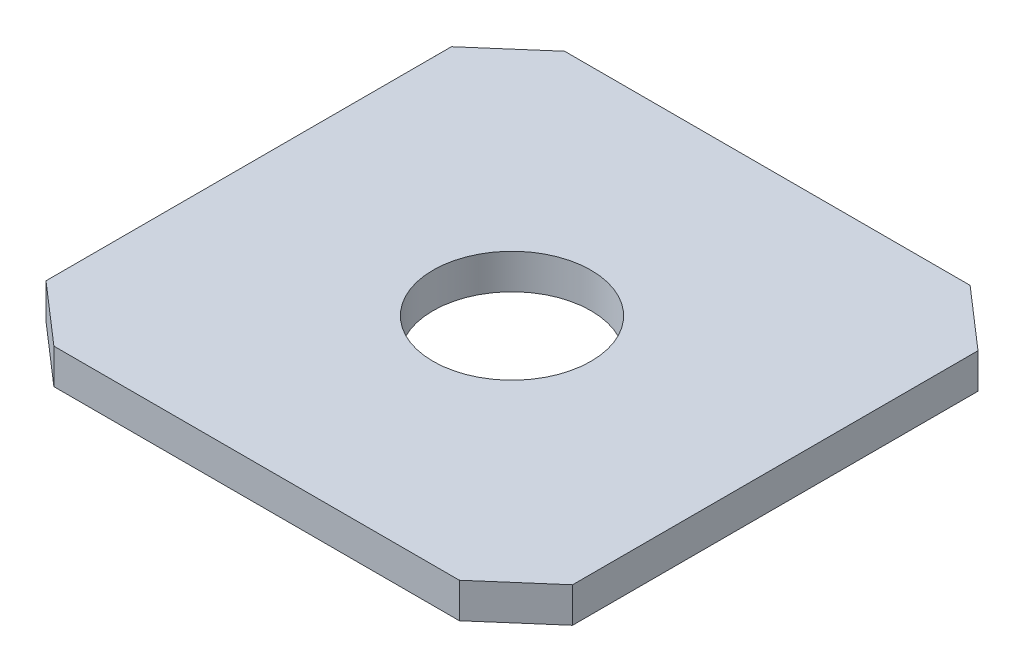
SolidWorks part; units mm, degrees
ref_plane "Front Plane" through (0, 0, 0) normal (0, 0, 1) x (1, 0, 0)
ref_plane "Top Plane" through (0, 0, 0) normal (0, 1, 0) x (1, 0, 0)
ref_plane "Right Plane" through (0, 0, 0) normal (1, 0, 0) x (0, 0, -1)
sketch "Sketch1" plane through (0, 0, 0) normal (0, 1, 0) x (1, 0, 0)
  line L8 (-10.1473, 19.7976) -> (-10.1473, -3.3024)
  line L9 (-10.1473, -3.3024) -> (-6.6973, -6.3024)
  line L10 (-6.6973, -6.3024) -> (16.4027, -6.3024)
  line L11 (16.4027, -6.3024) -> (19.8527, -3.3024)
  line L12 (19.8527, -3.3024) -> (19.8527, 19.7976)
  line L13 (19.8527, 19.7976) -> (16.4027, 22.7976)
  line L14 (16.4027, 22.7976) -> (-6.6973, 22.7976)
  line L15 (-6.6973, 22.7976) -> (-10.1473, 19.7976)
extrude "Boss-Extrude1" add sketch "Sketch1" along normal blind 2
sketch "Sketch2" plane through (0, 2, 0) normal (0, 1, 0) x (1, 0, 0)
  line L0 (-10.1473, 19.7976) -> (-10.1473, -3.3024) construction
  line L1 (16.4027, 22.7976) -> (-6.6973, 22.7976) construction
  circle A0 centre (4.8527, 8.2476) radius 4.5
  point P2 (-10.1473, 8.2476)
  point P3 (4.8527, 22.7976)
  dimension "D1" = 9
extrude "Cut-Extrude1" cut sketch "Sketch2" against normal through all
